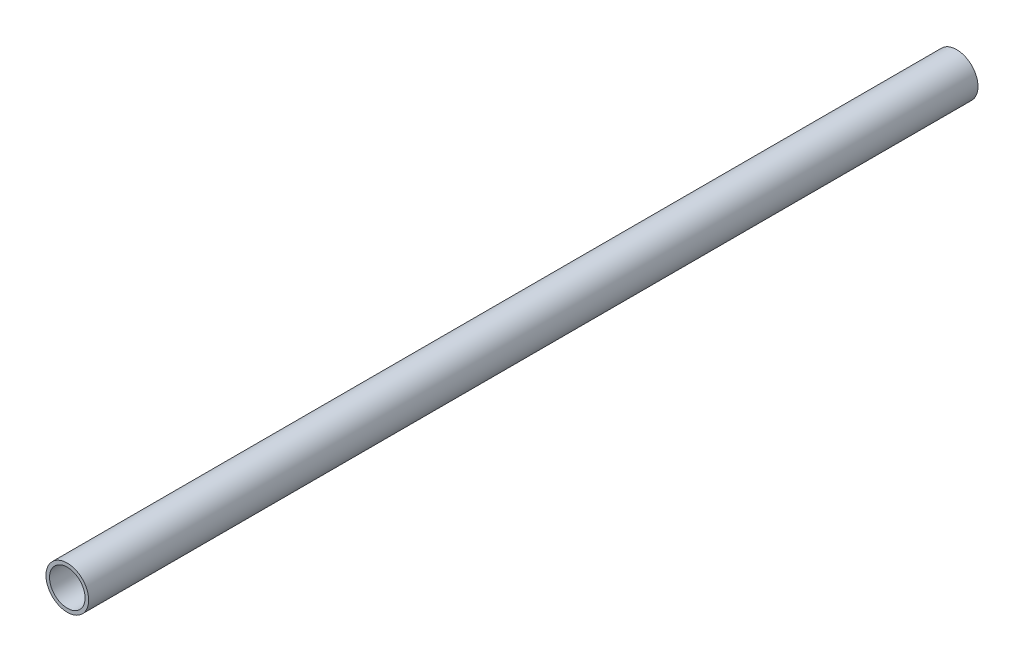
SolidWorks part; units mm, degrees
ref_plane "Front Plane" through (0, 0, 0) normal (0, 0, 1) x (1, 0, 0)
ref_plane "Top Plane" through (0, 0, 0) normal (0, 1, 0) x (1, 0, 0)
ref_plane "Right Plane" through (0, 0, 0) normal (1, 0, 0) x (0, 0, -1)
sketch "Sketch1" plane through (0, 0, 0) normal (0, 0, 1) x (1, 0, 0)
  circle A0 centre (0, 0) radius 6
  circle A1 centre (0, 0) radius 5
  dimension "D2" = 12
  dimension "D1" = 1
extrude "Boss-Extrude1" add sketch "Sketch1" along normal blind 250
sketch "Sketch2" plane through (0, 0, 0) normal (0, 1, 0) x (1, 0, 0)
  line L0 (-6, -125) -> (6, -125) construction
  line L1 (-6, 0) -> (-6, -250) construction
  line L2 (6, -250) -> (6, 0) construction
ref_plane "Plane1" through (0, 0, 125) normal (0, 0, 1) x (1, 0, 0)
